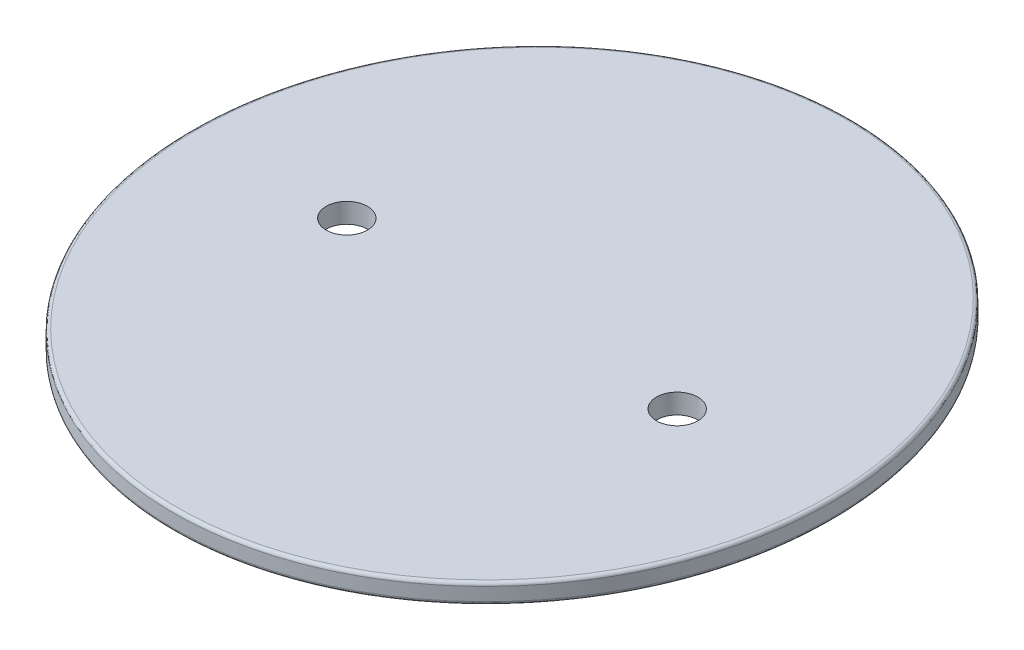
SolidWorks part; units mm, degrees
ref_plane "Front Plane" through (0, 0, 0) normal (0, 0, 1) x (1, 0, 0)
ref_plane "Top Plane" through (0, 0, 0) normal (0, 1, 0) x (1, 0, 0)
ref_plane "Right Plane" through (0, 0, 0) normal (1, 0, 0) x (0, 0, -1)
sketch "Sketch1" plane through (0, 0, 0) normal (0, 1, 0) x (1, 0, 0)
  line L0 (0, 30.2014) -> (0, 0) construction
  line L1 (0, 0) -> (14.2213, 0) construction
  circle A1 centre (-50, 0) radius 6.25
  circle A2 centre (50, 0) radius 6.25
  ellipse E0 centre (0, 0) end of major axis (0, 102.5) minor radius 96.9
  point P13 (0, 0)
  dimension "D3" = 12.5
  dimension "D4" = 100
  dimension "D1" = 102.5
  dimension "D2" = 96.9
extrude "Boss-Extrude1" add sketch "Sketch1" along normal mid plane 6
fillet "Fillet1" radius 1 2 edges at (0, -3, -102.5) (0, 3, -102.5)
